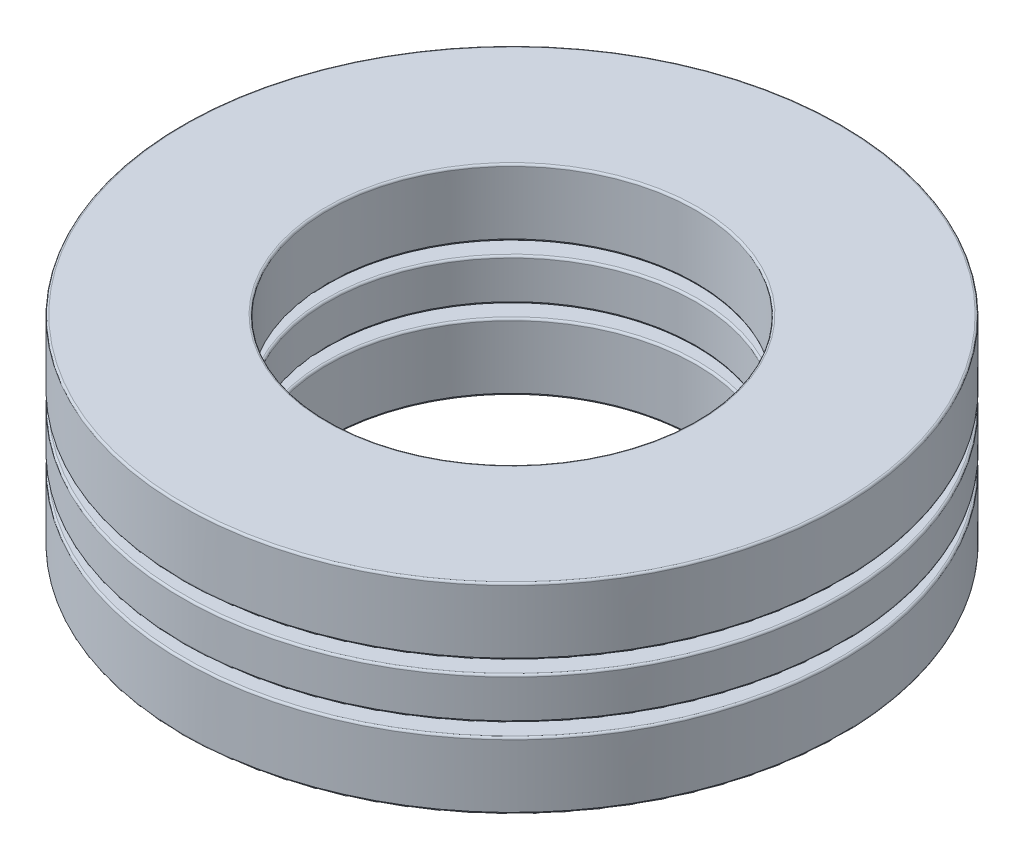
SolidWorks part; units mm, degrees
ref_plane "Front Plane" through (0, 0, 0) normal (0, 0, 1) x (1, 0, 0)
ref_plane "Top Plane" through (0, 0, 0) normal (0, 1, 0) x (1, 0, 0)
ref_plane "Right Plane" through (0, 0, 0) normal (1, 0, 0) x (0, 0, -1)
sketch "Sketch1" plane through (0, 0, 0) normal (1, 0, 0) x (0, 0, -1)
  line L0 (-14.2875, 0) -> (14.2875, 0) construction
  line L1 (0, -4.3434) -> (0, 4.3434) construction
  line L2 (-14.2875, 0.9049) -> (-7.9756, 0.9049)
  line L3 (-14.2875, 0.9049) -> (-14.2875, -0.9049)
  line L4 (-14.2875, -0.9049) -> (-7.9756, -0.9049)
  line L5 (-7.9756, 0.9049) -> (-7.9756, -0.9049)
  line L6 (-11.1315, 1.4478) -> (-11.1315, -1.4478) construction
  circle A0 centre (-11.1315, 0) radius 1.4478 construction
  point P13 (-11.1315, 0.9049)
  dimension "OD" = 28.575
  dimension "Shaft Dia" = 15.9512
  dimension "Th" = 8.6868
  dimension "D1" = 2.8956
  dimension "D2" = 1.8098
revolve "Revolve1" add sketch "Sketch1" angle 360 about L1
sketch "Sketch3" plane through (0, 0, 0) normal (1, 0, 0) x (0, 0, -1)
  line L0 (-11.1315, 1.4478) -> (-11.1315, -1.4478)
  arc A0 (-11.1315, 1.4478) -> (-11.1315, -1.4478) centre (-11.1315, 0) ccw
  circle A1 centre (-11.1315, 0) radius 1.4478 construction
revolve "Cut-Revolve1" cut sketch "Sketch3" angle 360 about L0
sketch "Sketch2" plane through (0, 0, 0) normal (1, 0, 0) x (0, 0, -1)
  line L0 (-11.1315, 1.4478) -> (-11.1315, -1.4478)
  arc A0 (-11.1315, 1.4478) -> (-11.1315, -1.4478) centre (-11.1315, 0) ccw
  circle A2 centre (-11.1315, 0) radius 1.4478 construction
revolve "Revolve2" add sketch "Sketch2" angle 360 about L0
ref_axis "Axis1" through (0, 4.3434, 0) along (0, -1, 0)
pattern_circular "CirPattern1" count 6 every 60 about axis through (0, 4.3434, 0) along (0, -1, 0) of bodies 187
pattern_circular "CirPattern2" count 6 every 60 about axis through (0, 0, 0) along (0, 1, 0) of "Cut-Revolve1"
sketch "Sketch4" plane through (0, 0, 0) normal (1, 0, 0) x (0, 0, -1)
  line L0 (-14.2875, 0.9049) -> (-14.2875, -0.9049) construction
  line L1 (-14.2875, 1.4478) -> (-7.9756, 1.4478)
  line L2 (-14.2875, 1.4478) -> (-14.2875, 4.3434)
  line L3 (-14.2875, 4.3434) -> (-7.9756, 4.3434)
  line L4 (-7.9756, 1.4478) -> (-7.9756, 4.3434)
  line L5 (-14.2875, -4.3434) -> (-7.9756, -4.3434)
  line L6 (-14.2875, -4.3434) -> (-14.2875, -1.4478)
  line L7 (-14.2875, -1.4478) -> (-7.9756, -1.4478)
  line L8 (-7.9756, -4.3434) -> (-7.9756, -1.4478)
  line L9 (-11.1315, 1.4478) -> (-11.1315, -1.4478) construction
  line L10 (-7.9756, 0.9049) -> (-7.9756, -0.9049) construction
  line L11 (0, 0) -> (-14.2875, 0) construction
  line L12 (-14.2875, 0) -> (14.2875, 0) construction
  dimension "Ht" = 8.6868
revolve "Revolve3" add sketch "Sketch4" angle 360 about L1
fillet "Fillet1" radius 0.0869 4 edges at (0, 1.4478, -7.9756) (0, 4.3434, -7.9756) (0, 1.4478, -14.2875) (0, 4.3434, -14.2875)
fillet "Fillet2" radius 0.0869 4 edges at (0, -0.9049, -7.9756) (0, 0.9049, -7.9756) (0, -0.9049, -14.2875) (0, 0.9049, -14.2875)
fillet "Fillet3" radius 0.0869 4 edges at (0, -4.3434, -7.9756) (0, -1.4478, -7.9756) (0, -4.3434, -14.2875) (0, -1.4478, -14.2875)
equation "\"D1@Sketch1\" = \"Th@Sketch1\"/3"
equation "\"D2@Sketch1\" = \"D1@Sketch1\"*.625"
equation "\"Balls@CirPattern1\" = \"OD@Sketch1\"*5"
equation "\"Angle@CirPattern1\" = 360/\"Balls@CirPattern1\""
equation "\"D1@CirPattern2\" = \"Balls@CirPattern1\""
equation "\"D2@CirPattern2\" = \"Angle@CirPattern1\""
equation "\"D1@Fillet1\" = \"Th@Sketch1\"*.01"
equation "\"D1@Fillet2\" = \"D1@Fillet1\""
equation "\"D1@Fillet3\" = \"D1@Fillet1\""
